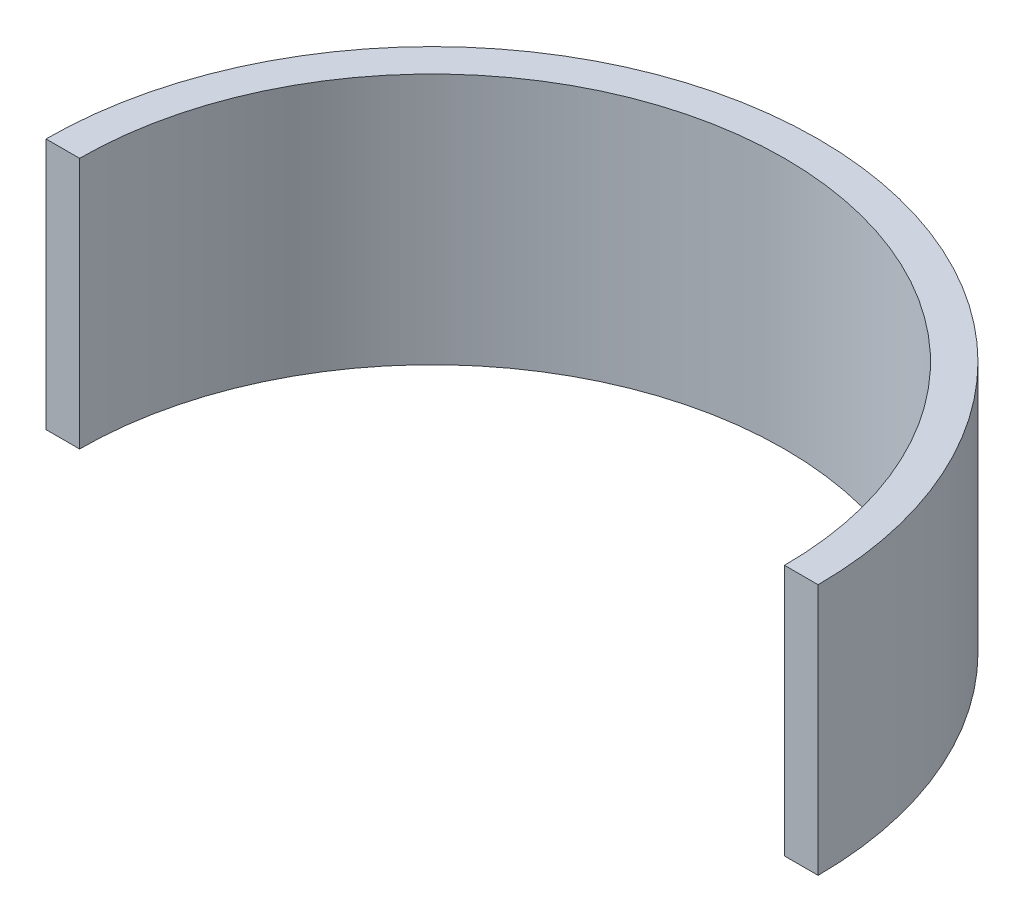
SolidWorks part; units mm, degrees
ref_plane "Front" through (0, 0, 0) normal (0, 0, 1) x (1, 0, 0)
ref_plane "Top" through (0, 0, 0) normal (0, 1, 0) x (1, 0, 0)
ref_plane "Right" through (0, 0, 0) normal (1, 0, 0) x (0, 0, -1)
sketch "草图1" plane through (0, 0, 0) normal (0, 1, 0) x (1, 0, 0)
  line L0 (-37.5979, 0) -> (41.4445, 0) construction
  line L1 (-46, 0) -> (-42, 0)
  line L2 (46, 0) -> (42, 0)
  arc A0 (-46, 0) -> (46, 0) centre (0, 0) cw
  arc A1 (-42, 0) -> (42, 0) centre (0, 0) cw
extrude "凸台-拉伸1" add sketch "草图1" along normal blind 30
